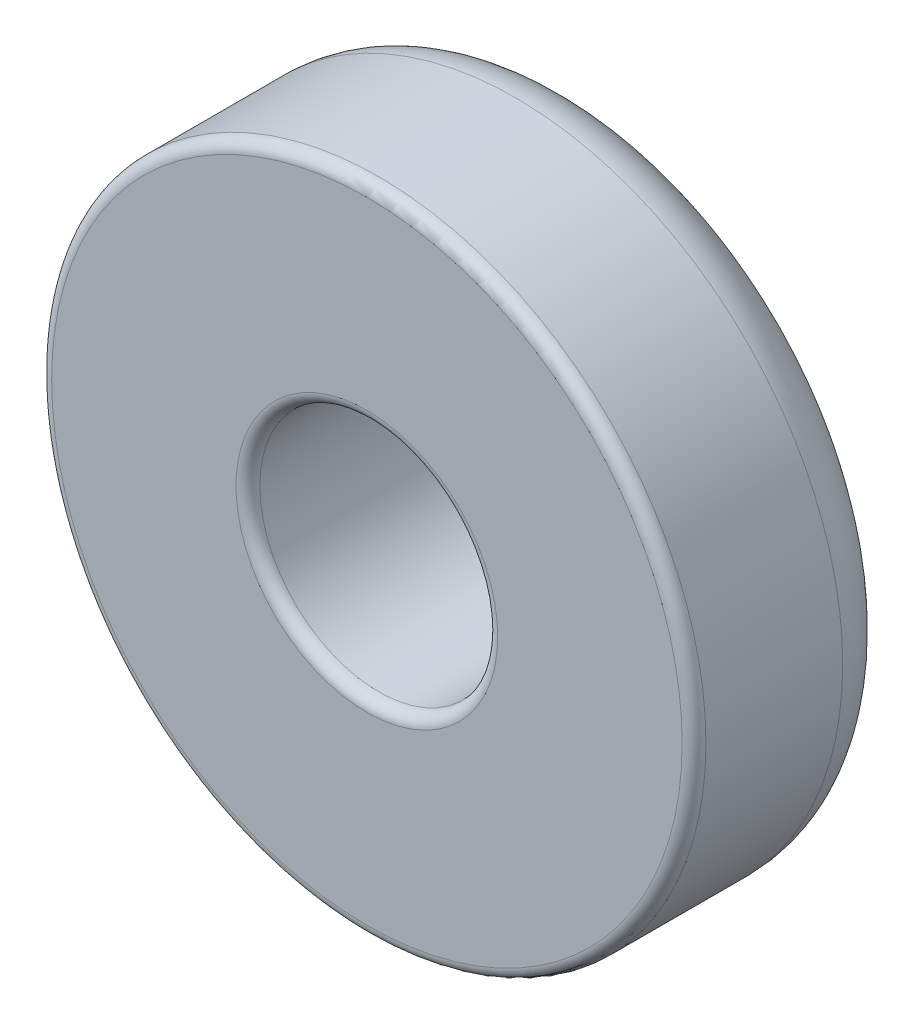
SolidWorks part; units mm, degrees
ref_plane "Front Plane" through (0, 0, 0) normal (0, 0, 1) x (1, 0, 0)
ref_plane "Top Plane" through (0, 0, 0) normal (0, 1, 0) x (1, 0, 0)
ref_plane "Right Plane" through (0, 0, 0) normal (1, 0, 0) x (0, 0, -1)
sketch "Sketch1" plane through (0, 0, 0) normal (0, 0, 1) x (1, 0, 0)
  circle A0 centre (0, 0) radius 1
  dimension "D1" = 2
extrude "Extrude-Thin2" add sketch "Sketch1" along normal blind 1.75 thin contours A0
fillet "Fillet1" radius 0.5 1 edges at (2.75, 0, 0)
fillet "Fillet2" radius 0.1 3 edges at (1, 0, 0) (1, 0, 1.75) (2.75, 0, 1.75)
